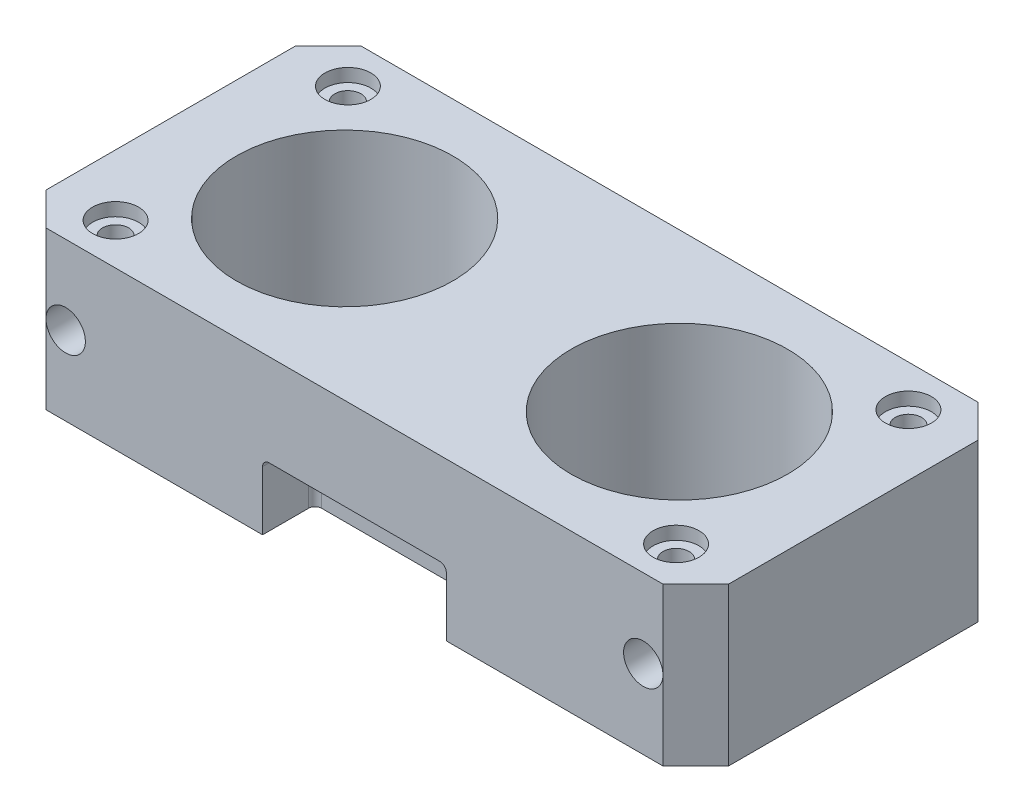
SolidWorks part; units mm, degrees
ref_plane "Front Plane" through (0, 0, 0) normal (0, 0, 1) x (1, 0, 0)
ref_plane "Top Plane" through (0, 0, 0) normal (0, 1, 0) x (1, 0, 0)
ref_plane "Right Plane" through (0, 0, 0) normal (1, 0, 0) x (0, 0, -1)
sketch "Sketch1" plane through (0, 0, 0) normal (0, 1, 0) x (1, 0, 0)
  line L0 (-12.75, 0) -> (12.75, 0) construction
  line L1 (-26, 12) -> (26, 12)
  line L2 (-26, 12) -> (-26, -12)
  line L3 (-26, -12) -> (26, -12)
  line L4 (26, 12) -> (26, -12)
  line L5 (-26, 12) -> (26, -12) construction
  line L6 (-26, -12) -> (26, 12) construction
  circle A0 centre (12.75, 0) radius 8.25
  circle A1 centre (-12.75, 0) radius 8.25
  point P0 (0, 0)
  point P9 (0, 0)
  dimension "D3" = 16.5
  dimension "D1" = 52
  dimension "D2" = 24
  dimension "D4" = 25.5
extrude "Boss-Extrude1" add sketch "Sketch1" along normal blind 12
sketch "Sketch2" plane through (0, 12, 0) normal (0, 1, 0) x (1, 0, 0)
  line L1 (-21.35, 8.85) -> (21.35, 8.85) construction
  line L2 (-21.35, 8.85) -> (-21.35, -8.85) construction
  line L3 (-21.35, -8.85) -> (21.35, -8.85) construction
  line L4 (21.35, 8.85) -> (21.35, -8.85) construction
  line L5 (-21.35, 8.85) -> (21.35, -8.85) construction
  line L6 (-21.35, -8.85) -> (21.35, 8.85) construction
  circle A0 centre (-21.35, 8.85) radius 1
  circle A1 centre (21.35, 8.85) radius 1
  circle A2 centre (21.35, -8.85) radius 1
  circle A3 centre (-21.35, -8.85) radius 1
  point P0 (0, 0)
  dimension "D3" = 2
  dimension "D1" = 17.7
  dimension "D2" = 42.7
extrude "Cut-Extrude1" cut sketch "Sketch2" against normal through all
sketch "Sketch3" plane through (0, 12, 0) normal (0, 1, 0) x (1, 0, 0)
  circle A20 centre (-21.35, 8.85) radius 1.75
  circle A21 centre (21.35, 8.85) radius 1.75
  circle A23 centre (21.35, -8.85) radius 1.75
  circle A24 centre (-21.35, -8.85) radius 1.75
  dimension "D1" = 3.5
extrude "Cut-Extrude2" cut sketch "Sketch3" against normal blind 1
sketch "Sketch4" plane through (0, 0, 0) normal (0, -1, 0) x (1, 0, 0)
  line L0 (26, -12) -> (-26, -12) construction
  line L1 (-6, -12) -> (6, -12)
  line L2 (-6, -12) -> (-6, -5)
  line L3 (-6, -5) -> (6, -5)
  line L4 (6, -12) -> (6, -5)
  line L5 (0, -5) -> (0, 0)
  line M14 (-26, -12) -> (26, -12)
  dimension "D1" = 7
  dimension "D2" = 12
extrude "Cut-Extrude3" cut sketch "Sketch4" against normal blind 5 contours L4 L3 L2 M14
fillet "Fillet3" radius 0.5 5 edges at (-6, 5, -8.5) (6, 5, -8.5) (6, 2.5, -5) (0, 5, -5) (-6, 2.5, -5)
chamfer "Chamfer1" distance 2.5 4 edges at (26, 6, 12) (26, 6, -12) (-26, 6, -12) (-26, 6, 12)
sketch "Sketch5" plane through (0, 0, 0) normal (0, -1, 0) x (1, 0, 0)
  line L0 (-23.5, 12) -> (23.5, 12) construction
  line L1 (-7, 16) -> (7, 16)
  line L2 (-7, 16) -> (-7, 8)
  line L3 (-7, 8) -> (7, 8)
  line L4 (7, 16) -> (7, 8)
  line L5 (-7, 16) -> (7, 8) construction
  line L6 (-7, 8) -> (7, 16) construction
  point P0 (0, 12)
  dimension "D1" = 8
  dimension "D2" = 14
extrude "Cut-Extrude4" cut sketch "Sketch5" against normal up to surface (5 mm away) up to face at (0, 5, -8.75)
fillet "Fillet4" radius 0.5 5 edges at (7, 2.5, 8) (7, 5, 10) (-7, 5, 10) (-7, 2.5, 8) (0, 5, 8)
hole_wizard "CSK for M3 SFHCS2" positions "Sketch14" profile "Sketch15" countersink size "M3" standard "ANSI Metric"
sketch "Sketch14" plane through (-1333.2473, 660.683, 18.5) normal (0, 0, 1) x (0, -1, 0)
  point P0 (654.683, 1355.2473)
  point P2 (654.683, 1311.2473)
  point P24 (736.683, 1355.2473)
  point P25 (736.683, 1311.2473)
sketch "Sketch15" plane through (22, 6, 18.5) normal (1, 0, 0) x (0, -1, 0)
  line L0 (0, 0) -> (0, 10.9013)
  line L1 (0, 10.9013) -> (1.5, 10)
  line L2 (1.5, 10) -> (1.5, 1.7)
  line L3 (1.5, 1.7) -> (3.2, 0)
  line L4 (3.2, 0) -> (0, 0)
  line L5 (-1.5, 1.7) -> (-3.2, 0) construction
  line L6 (0, 10.9013) -> (-1.5, 10) construction
  line L7 (0, -6.35) -> (0, 107.95) construction
  dimension "Hole Dia." = 3
  dimension "Hole Depth" = 10
  dimension "Near C'Sink Dia." = 6.4
  dimension "Near C'Sink Angle" = 90
  dimension "Drill Angle" = 118
hole_wizard "CSK for M3 SFHCS3" positions "Sketch16" profile "Sketch17" countersink size "M3" standard "ANSI Metric"
sketch "Sketch16" plane through (1333.2473, -730.683, 18.5) normal (0, 0, 1) x (0, 1, 0)
  point P0 (654.683, 1355.2473)
  point P2 (654.683, 1311.2473)
  point P24 (736.683, 1355.2473)
  point P25 (736.683, 1311.2473)
sketch "Sketch17" plane through (-22, -76, 18.5) normal (1, 0, 0) x (0, -1, 0)
  line L0 (0, 0) -> (0, 10.9013)
  line L1 (0, 10.9013) -> (1.5, 10)
  line L2 (1.5, 10) -> (1.5, 1.7)
  line L3 (1.5, 1.7) -> (3.2, 0)
  line L4 (3.2, 0) -> (0, 0)
  line L5 (-1.5, 1.7) -> (-3.2, 0) construction
  line L6 (0, 10.9013) -> (-1.5, 10) construction
  line L7 (0, -6.35) -> (0, 107.95) construction
  dimension "Hole Dia." = 3
  dimension "Hole Depth" = 10
  dimension "Near C'Sink Dia." = 6.4
  dimension "Near C'Sink Angle" = 90
  dimension "Drill Angle" = 118
